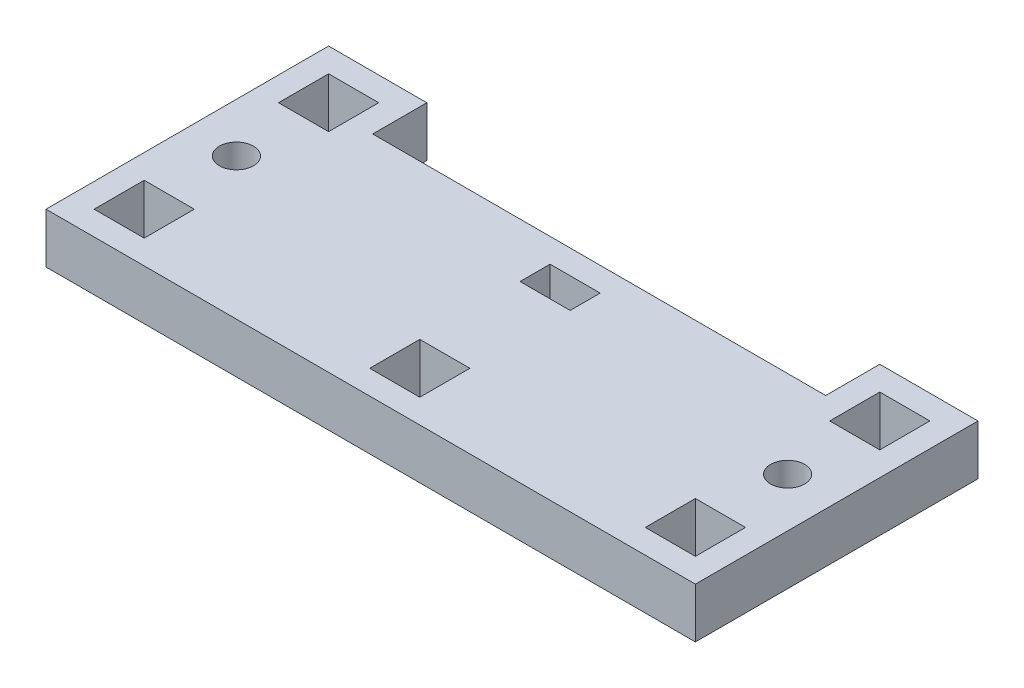
SolidWorks part; units mm, degrees
ref_plane "Front Plane" through (0, 0, 0) normal (0, 0, 1) x (1, 0, 0)
ref_plane "Top Plane" through (0, 0, 0) normal (0, 1, 0) x (1, 0, 0)
ref_plane "Right Plane" through (0, 0, 0) normal (1, 0, 0) x (0, 0, -1)
sketch "Sketch1" plane through (0, 0, 0) normal (0, 1, 0) x (1, 0, 0)
  line L0 (-41.148, 0) -> (41.148, 0) construction
  line L1 (-41.148, -17.907) -> (41.148, -17.907)
  line L2 (-41.148, -17.907) -> (-41.148, 17.907)
  line L3 (-41.148, 17.907) -> (-28.702, 17.907)
  line L4 (41.148, -17.907) -> (41.148, 17.907)
  line L5 (-41.148, -17.907) -> (41.148, 17.907) construction
  line L6 (-41.148, 17.907) -> (41.148, -17.907) construction
  line L7 (0, 11.049) -> (0, -17.907) construction
  line L8 (-28.702, 17.907) -> (-28.702, 11.049)
  line L9 (-28.702, 11.049) -> (28.702, 11.049)
  line L10 (-3.175, -8.509) -> (3.175, -8.509)
  line L11 (-3.175, -8.509) -> (-3.175, -14.859)
  line L12 (-3.175, -14.859) -> (3.175, -14.859)
  line L13 (3.175, -8.509) -> (3.175, -14.859)
  line L14 (-3.175, -8.509) -> (3.175, -14.859) construction
  line L15 (-3.175, -14.859) -> (3.175, -8.509) construction
  line L16 (-3.175, 4.191) -> (3.175, 4.191)
  line L17 (-3.175, 4.191) -> (-3.175, 8.001)
  line L18 (-3.175, 8.001) -> (3.175, 8.001)
  line L19 (3.175, 4.191) -> (3.175, 8.001)
  line L20 (-3.175, 4.191) -> (3.175, 8.001) construction
  line L21 (-3.175, 8.001) -> (3.175, 4.191) construction
  line L22 (28.702, 11.049) -> (28.702, 17.907)
  line L23 (28.702, 17.907) -> (41.148, 17.907)
  point P0 (0, 0)
  point P12 (0, -11.684)
  point P17 (0, 6.096)
  line B0 (31.75, 8.509) -> (38.1, 8.509)
  line B1 (31.75, 8.509) -> (31.75, 14.859)
  line B2 (31.75, 14.859) -> (38.1, 14.859)
  line B3 (38.1, 8.509) -> (38.1, 14.859)
  line B4 (38.1, -8.509) -> (38.1, -14.859)
  line B5 (31.75, -14.859) -> (38.1, -14.859)
  line B6 (31.75, -8.509) -> (31.75, -14.859)
  line B7 (31.75, -8.509) -> (38.1, -8.509)
  circle B8 centre (34.925, 0) radius 2.159
  line B9 (-31.75, 8.509) -> (-38.1, 8.509)
  line B10 (-31.75, 8.509) -> (-31.75, 14.859)
  line B11 (-31.75, 14.859) -> (-38.1, 14.859)
  line B12 (-38.1, 8.509) -> (-38.1, 14.859)
  line B13 (-38.1, -8.509) -> (-38.1, -14.859)
  line B14 (-31.75, -14.859) -> (-38.1, -14.859)
  line B15 (-31.75, -8.509) -> (-31.75, -14.859)
  line B16 (-31.75, -8.509) -> (-38.1, -8.509)
  circle B17 centre (-34.925, 0) radius 2.159
  dimension "D1" = 3.048
  dimension "D2" = 3.048
  dimension "D3" = 63.5
  dimension "D4" = 3.048
  dimension "D5" = 6.35
  dimension "D6" = 12.7
  dimension "D7" = 3.81
  dimension "D8" = 3.048
  dimension "D9" = 3.048
  dimension "D10" = 3.048
sketch_block_instance "Female T-Slot Assembly-1"
sketch_block "Female T-Slot Assembly" parameters "D4"=4.318, "D1"=6.35, "D2"=6.35, "D3"=6.35
sketch_block_instance "Female T-Slot Assembly-3"
extrude "Boss-Extrude1" add sketch "Sketch1" along normal blind 6.35
